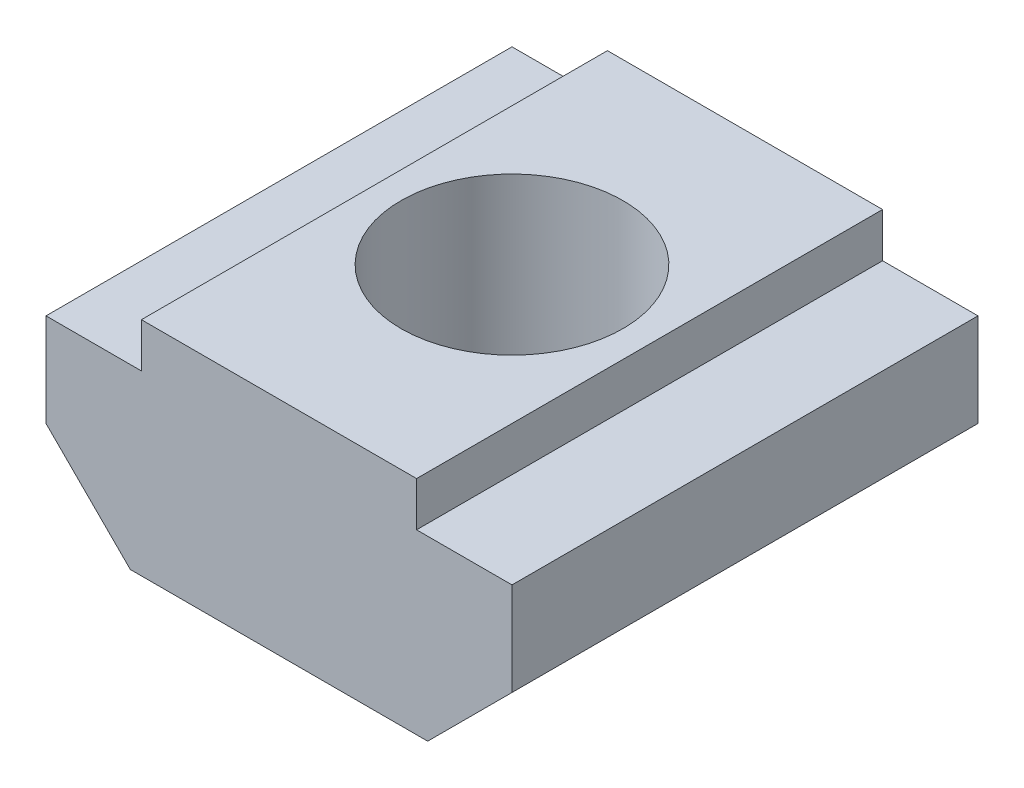
SolidWorks part; units mm, degrees
ref_plane "Front Plane" through (0, 0, 0) normal (0, 0, 1) x (1, 0, 0)
ref_plane "Top Plane" through (0, 0, 0) normal (0, 1, 0) x (1, 0, 0)
ref_plane "Right Plane" through (0, 0, 0) normal (1, 0, 0) x (0, 0, -1)
sketch "Sketch2" plane through (0, 0, 0) normal (0, 0, 1) x (1, 0, 0)
  line L0 (-5.25, 1.5) -> (5.25, 1.5)
  line L1 (-5.25, -2.5) -> (5.25, -2.5)
  line L2 (-5.25, -2.5) -> (-5.25, 2.5)
  line L3 (-5.25, 2.5) -> (5.25, 2.5)
  line L4 (5.25, -2.5) -> (5.25, 2.5)
  line L5 (-5.25, -2.5) -> (5.25, 2.5) construction
  line L6 (-5.25, 2.5) -> (5.25, -2.5) construction
  line L7 (-3.1, 2.5) -> (3.1, 2.5)
  line L8 (-3.1, 2.5) -> (-3.1, 1.5)
  line L9 (-3.1, 1.5) -> (3.1, 1.5)
  line L10 (3.1, 2.5) -> (3.1, 1.5)
  line L11 (-3.35, -2.5) -> (-5.25, -0.6)
  line L12 (5.25, -0.6) -> (3.35, -2.5)
  point P0 (0, 0)
  point P10 (0, 1.5)
  dimension "D1" = 10.5
  dimension "D2" = 5
  dimension "D3" = 1
  dimension "D4" = 6.2
  dimension "D5" = 3.35
  dimension "D6" = 45
  dimension "D7" = 45
extrude "Boss-Extrude1" add sketch "Sketch2" along normal blind 10.5 contours L12 L4 L0 L2 L11 L1 | L10 L3 L8 L0
sketch "Sketch3" plane through (0, 2.5, 0) normal (0, 1, 0) x (1, 0, 0)
  line L0 (-3.1, 0) -> (3.1, -10.5) construction
  line L4 (3.1, 0) -> (-3.1, 0)
  line L5 (-3.1, 0) -> (-3.1, -10.5)
  line L6 (-3.1, -10.5) -> (3.1, -10.5)
  line L7 (3.1, -10.5) -> (3.1, 0)
  line L8 (3.1, 0) -> (-3.1, 0)
  line L9 (-3.1, 0) -> (-3.1, -10.5)
  line L10 (-3.1, -10.5) -> (3.1, -10.5)
  line L11 (3.1, -10.5) -> (3.1, 0)
  circle A0 centre (0, -5.25) radius 2.5
  dimension "D2" = 5
  dimension "D1" = 0
extrude "Cut-Extrude1" cut sketch "Sketch3" against normal through all contours L0 A0 | A0 L0
